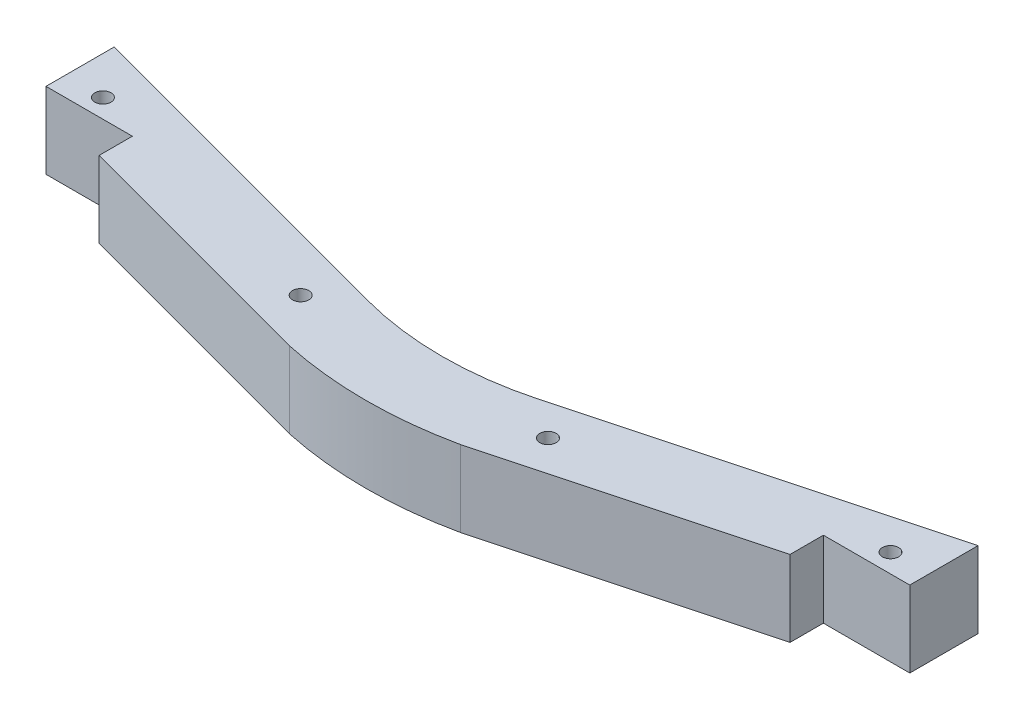
SolidWorks part; units mm, degrees
ref_plane "Front Plane" through (0, 0, 0) normal (0, 0, 1) x (1, 0, 0)
ref_plane "Top Plane" through (0, 0, 0) normal (0, 1, 0) x (1, 0, 0)
ref_plane "Right Plane" through (0, 0, 0) normal (1, 0, 0) x (0, 0, -1)
sketch "Sketch1" plane through (0, 0, 0) normal (0, 1, 0) x (1, 0, 0)
  line L0 (0, 0) -> (0, -62.8376) construction
  line L1 (-16.84, -62.8376) -> (16.84, -62.8376) construction
  line L2 (-16.84, -62.8376) -> (-16.84, -78.2638)
  line L3 (-16.84, -78.2638) -> (16.84, -78.2638) construction
  line L4 (16.84, -62.8376) -> (16.84, -78.2638)
  circle A0 centre (0, 0) radius 65.055
  circle A1 centre (0, 0) radius 80.055
  dimension "D1" = 130.11
  dimension "D3" = 33.68
  dimension "D2" = 15
extrude "Boss-Extrude1" add sketch "Sketch1" along normal blind 15 contours L2 A1 L4 A0
sketch "Sketch2" plane through (0, 15, 0) normal (0, 1, 0) x (1, 0, 0)
  line L0 (16.84, -62.8376) -> (84.9978, -44.5748)
  line L1 (84.9978, -44.5748) -> (84.9978, -60.0009)
  line L2 (84.9978, -60.0009) -> (16.84, -78.2638)
  line L3 (16.84, -78.2638) -> (16.84, -62.8376)
  line L8 (84.9978, -60.0009) -> (69.9978, -60.0009) construction
  line L9 (69.9978, -60.0009) -> (69.9978, -64.0202) construction
  line L10 (84.9978, -52.2879) -> (16.84, -70.5507) construction
  line L11 (67.9978, -64.5561) -> (67.9978, -58.0009)
  line L12 (67.9978, -58.0009) -> (84.9978, -58.0009)
  line L13 (0, -65.055) -> (0, -80.055) construction
  line L14 (-84.9978, -44.5748) -> (-84.9978, -60.0009)
  line L15 (-67.9978, -64.5561) -> (-67.9978, -58.0009)
  line L16 (-67.9978, -58.0009) -> (-84.9978, -58.0009)
  line L17 (-84.9978, -60.0009) -> (-16.84, -78.2638)
  line L18 (-16.84, -78.2638) -> (-16.84, -62.8376)
  line L19 (-16.84, -62.8376) -> (-84.9978, -44.5748)
  arc A0 (-16.84, -62.8376) -> (16.84, -62.8376) centre (0, 0) ccw construction
  arc A1 (-16.84, -78.2638) -> (16.84, -78.2638) centre (0, 0) ccw construction
  circle A2 centre (24.3357, -68.5422) radius 1.6
  circle A3 centre (77.4978, -54.2975) radius 1.6
  circle A4 centre (-77.4978, -54.2975) radius 1.6
  circle A5 centre (-24.3357, -68.5422) radius 1.6
  point P3 (0, 0)
  point P11 (0, 0)
  point P13 (0, 0)
  line M11 (-16.84, -62.8376) -> (-16.84, -78.2638)
  line M13 (16.84, -78.2638) -> (16.84, -62.8376)
  dimension "D1" = 68.1578
  dimension "D6" = 3.2
  dimension "D7" = 7.5
  dimension "D8" = 7.4957
  dimension "D2" = 75
  dimension "D3" = 15
  dimension "D4" = 2
  dimension "D5" = 2
extrude "Boss-Extrude2" add sketch "Sketch2" against normal up to surface (15 mm away) contours L19 L14 L16 L15 L17 A4 A5 M11 | L11 L12 L1 L0 L2 A3 A2 M13 up to face at (0, 0, 71.5528)
